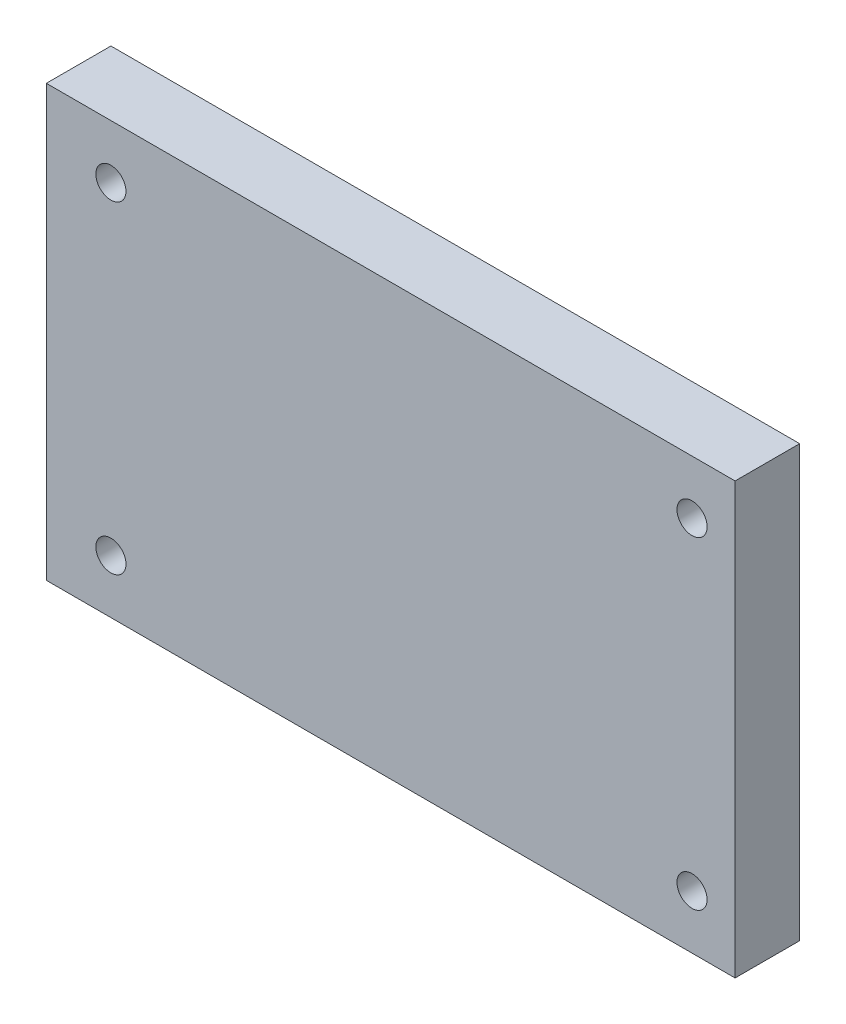
SolidWorks part; units mm, degrees
ref_plane "Plan de face" through (0, 0, 0) normal (0, 0, 1) x (1, 0, 0)
ref_plane "Plan de dessus" through (0, 0, 0) normal (0, 1, 0) x (1, 0, 0)
ref_plane "Plan de droite" through (0, 0, 0) normal (1, 0, 0) x (0, 0, -1)
sketch "Esquisse1" plane through (0, 0, 0) normal (0, 0, 1) x (1, 0, 0)
  line L1 (16, -10) -> (-16, -10)
  line L2 (16, -10) -> (16, 10)
  line L3 (16, 10) -> (-16, 10)
  line L4 (-16, -10) -> (-16, 10)
  line L5 (16, -10) -> (-16, 10) construction
  line L6 (16, 10) -> (-16, -10) construction
  point P0 (0, 0)
  dimension "D1" = 32
  dimension "D2" = 20
extrude "Boss.-Extru.1" add sketch "Esquisse1" along normal blind 3
sketch "Esquisse2" plane through (0, 0, 3) normal (0, 0, 1) x (1, 0, 0)
  line L0 (16, 10) -> (-16, 10) construction
  line L1 (-16, 10) -> (-16, -10) construction
  line L2 (-21.8164, 0) -> (23.3779, 0) construction
  circle A0 centre (-13, 7.5) radius 0.7
  circle A3 centre (14, 7.5) radius 0.7
  circle A4 centre (14, -7.5) radius 0.7
  circle A5 centre (-13, -7.5) radius 0.7
  dimension "D1" = 1.4
  dimension "D4" = 1.4
  dimension "D2" = 2.5
  dimension "D3" = 3
  dimension "D7" = 27
extrude "Enlèv. mat.-Extru.1" cut sketch "Esquisse2" against normal through all
